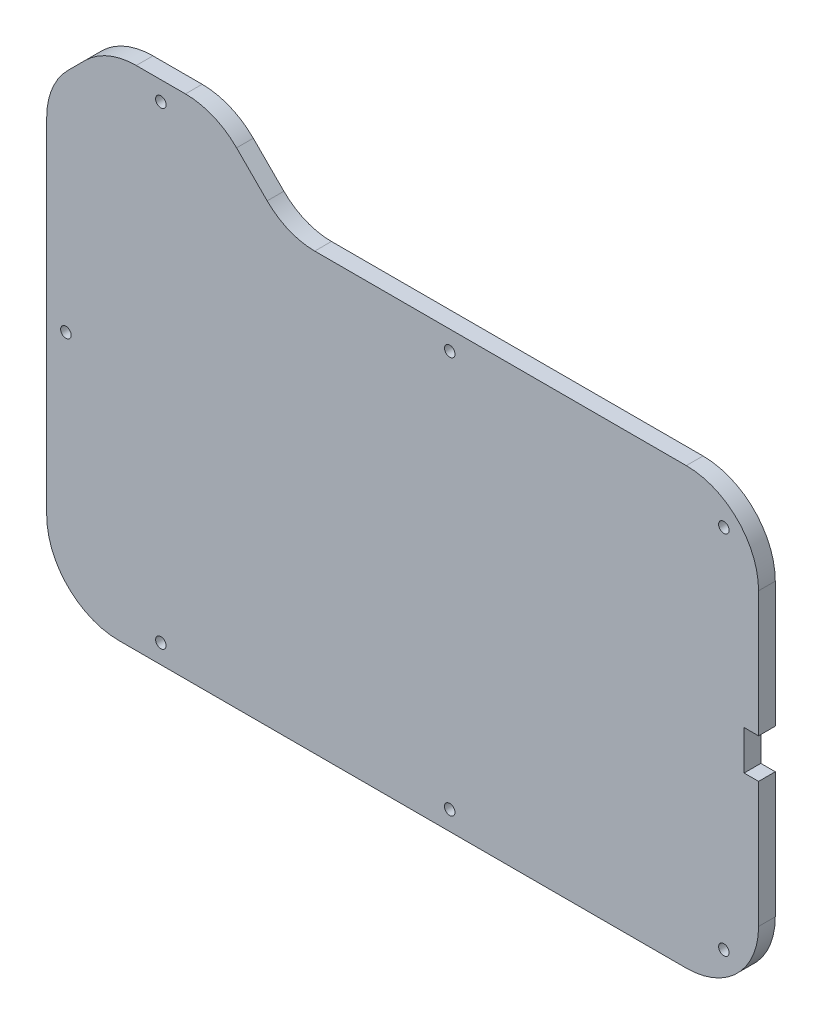
SolidWorks part; units mm, degrees
ref_plane "Front Plane" through (0, 0, 0) normal (0, 0, 1) x (1, 0, 0)
ref_plane "Top Plane" through (0, 0, 0) normal (0, 1, 0) x (1, 0, 0)
ref_plane "Right Plane" through (0, 0, 0) normal (1, 0, 0) x (0, 0, -1)
sketch "Sketch1" plane through (0, 0, 0) normal (0, 0, 1) x (1, 0, 0)
  line L51 (143.9081, 20.4605) -> (143.9081, 75.7605) construction
  line L52 (130.0581, 89.6105) -> (59.3752, 89.6105) construction
  line L53 (50.3949, 93.3302) -> (44.5712, 99.1539) construction
  line L54 (34.7778, 103.2105) -> (25.4148, 103.2105) construction
  line L55 (15.6214, 99.1539) -> (12.3411, 95.8737) construction
  line L56 (8.2846, 86.0802) -> (8.2846, 20.4605) construction
  line L57 (22.1346, 6.6105) -> (130.0581, 6.6105) construction
  line L58 (143.8081, 20.4605) -> (143.8081, 44.3605)
  line L59 (130.0581, 89.5105) -> (59.3752, 89.5105)
  line L60 (50.3242, 93.2595) -> (44.5005, 99.0832)
  line L61 (34.7778, 103.1105) -> (25.4148, 103.1105)
  line L62 (15.6921, 99.0832) -> (12.4118, 95.803)
  line L63 (8.3846, 86.0802) -> (8.3846, 20.4605)
  line L64 (22.1346, 6.7105) -> (130.0581, 6.7105)
  line L65 (143.8081, 48.1105) -> (141.0581, 48.1105) construction
  line L66 (141.0581, 44.3605) -> (141.0581, 51.8605)
  line L67 (141.0581, 51.8605) -> (143.8081, 51.8605)
  line L68 (141.0581, 44.3605) -> (143.8081, 44.3605)
  line L69 (143.8081, 51.8605) -> (143.8081, 75.7605)
  line L70 (143.8081, 51.8605) -> (143.8081, 44.3605) construction
  arc A71 (130.0581, 6.6105) -> (143.9081, 20.4605) centre (130.0581, 20.4605) ccw construction
  arc A72 (143.9081, 75.7605) -> (130.0581, 89.6105) centre (130.0581, 75.7605) ccw construction
  arc A73 (50.3949, 93.3302) -> (59.3752, 89.6105) centre (59.3752, 102.3105) ccw construction
  arc A74 (44.5712, 99.1539) -> (34.7778, 103.2105) centre (34.7778, 89.3605) ccw construction
  arc A75 (25.4148, 103.2105) -> (15.6214, 99.1539) centre (25.4148, 89.3605) ccw construction
  arc A76 (12.3411, 95.8737) -> (8.2846, 86.0802) centre (22.1346, 86.0802) ccw construction
  arc A77 (8.2846, 20.4605) -> (22.1346, 6.6105) centre (22.1346, 20.4605) ccw construction
  circle A78 centre (12.0346, 52.4704) radius 1
  circle A79 centre (30.0963, 99.4605) radius 1
  circle A80 centre (85.0537, 85.8605) radius 1
  circle A81 centre (137.1998, 82.9023) radius 1
  circle A82 centre (137.1998, 13.3187) radius 1
  circle A83 centre (85.0537, 10.3605) radius 1
  circle A84 centre (30.0963, 10.3605) radius 1
  arc A85 (143.8081, 75.7605) -> (130.0581, 89.5105) centre (130.0581, 75.7605) ccw
  arc A86 (50.3242, 93.2595) -> (59.3752, 89.5105) centre (59.3752, 102.3105) ccw
  arc A87 (44.5005, 99.0832) -> (34.7778, 103.1105) centre (34.7778, 89.3605) ccw
  arc A88 (25.4148, 103.1105) -> (15.6921, 99.0832) centre (25.4148, 89.3605) ccw
  arc A89 (12.4118, 95.803) -> (8.3846, 86.0802) centre (22.1346, 86.0802) ccw
  arc A90 (8.3846, 20.4605) -> (22.1346, 6.7105) centre (22.1346, 20.4605) ccw
  arc A91 (130.0581, 6.7105) -> (143.8081, 20.4605) centre (130.0581, 20.4605) ccw
  point P125 (141.0581, 48.1105)
extrude "Boss-Extrude1" add sketch "Sketch1" along normal blind 3.175
